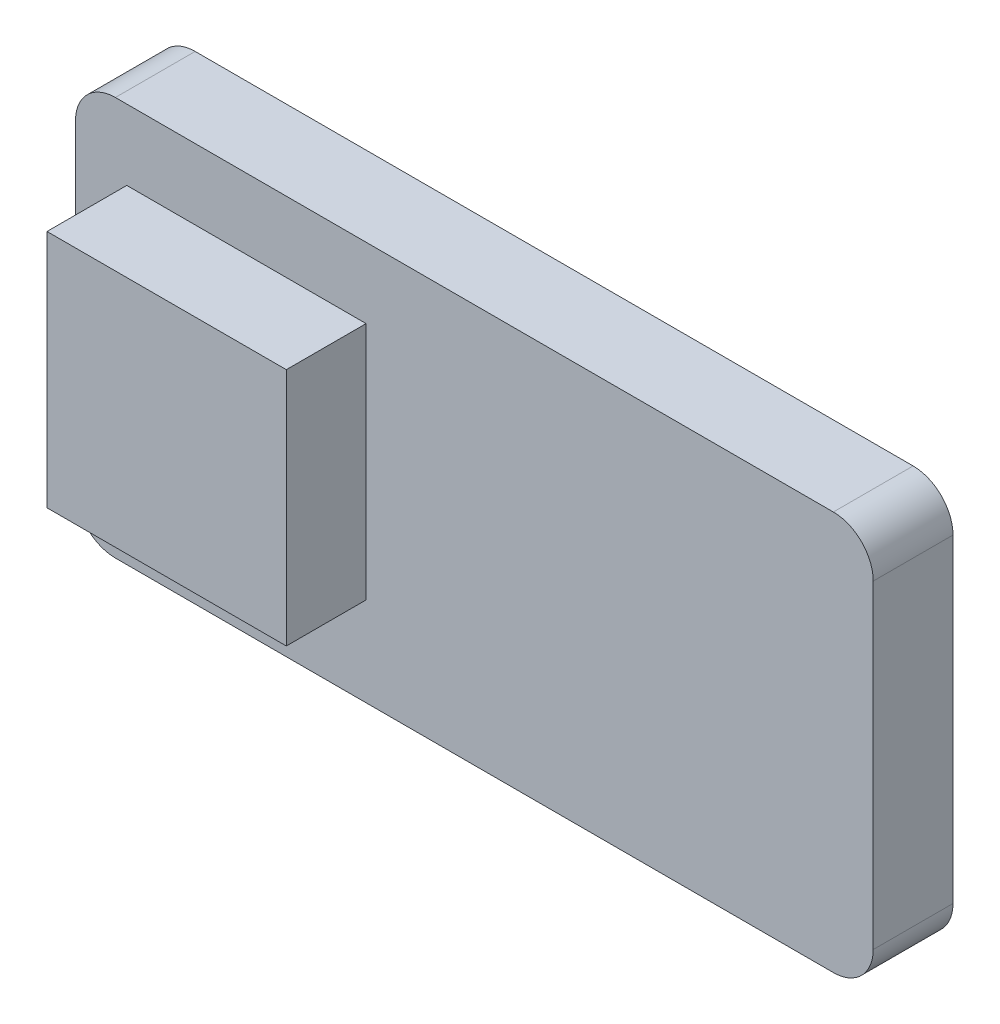
SolidWorks part; units mm, degrees
ref_plane "Front Plane" through (0, 0, 0) normal (0, 0, 1) x (1, 0, 0)
ref_plane "Top Plane" through (0, 0, 0) normal (0, 1, 0) x (1, 0, 0)
ref_plane "Right Plane" through (0, 0, 0) normal (1, 0, 0) x (0, 0, -1)
sketch "Sketch1" plane through (0, 0, 0) normal (0, 0, 1) x (1, 0, 0)
  line L0 (0, -61.6421) -> (0, 0) construction
  line L1 (-10, -22.0965) -> (10, -22.0965)
  line L2 (-10, -22.0965) -> (-10, -32.0965)
  line L3 (-10, -32.0965) -> (10, -32.0965)
  line L4 (10, -22.0965) -> (10, -32.0965)
  line L5 (-10, -27.0965) -> (10, -27.0965) construction
  ellipse E0 centre (0, -59.529) end of major axis (-5, -59.529) minor radius 2.1131 construction
  dimension "D1" = 10
  dimension "D2" = 20
  dimension "D3" = 10
extrude "Boss-Extrude1" add sketch "Sketch1" along normal blind 2
fillet "Fillet1" radius 1 4 edges at (-10, -32.0965, 1) (-10, -22.0965, 1) (10, -32.0965, 1) (10, -22.0965, 1)
sketch "Sketch2" plane through (0, 0, 2) normal (0, 0, 1) x (1, 0, 0)
  line L1 (-2.7145, -23.863) -> (-8.7145, -23.863)
  line L2 (-2.7145, -23.863) -> (-2.7145, -29.863)
  line L3 (-2.7145, -29.863) -> (-8.7145, -29.863)
  line L4 (-8.7145, -23.863) -> (-8.7145, -29.863)
  dimension "D1" = 6
  dimension "D2" = 6
extrude "Boss-Extrude2" add sketch "Sketch2" along normal blind 2
